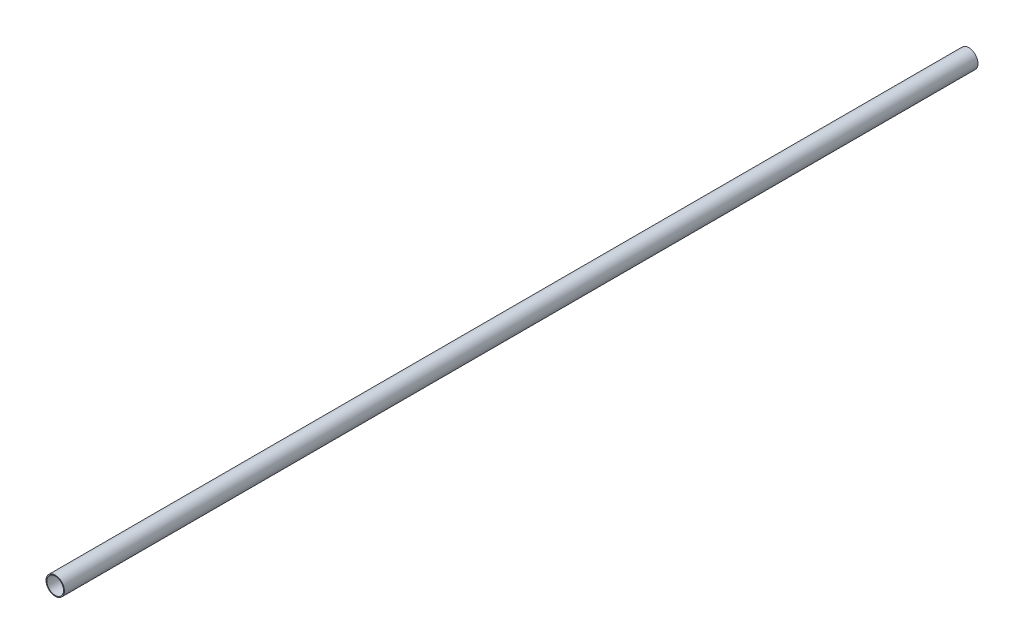
SolidWorks part; units mm, degrees
material "Thornel Mat VMA"
ref_plane "Front" through (0, 0, 0) normal (0, 0, 1) x (1, 0, 0)
ref_plane "Top" through (0, 0, 0) normal (0, 1, 0) x (1, 0, 0)
ref_plane "Right" through (0, 0, 0) normal (1, 0, 0) x (0, 0, -1)
sketch "Sketch1" plane through (0, 0, 0) normal (0, 0, 1) x (1, 0, 0)
  circle A0 centre (0, 0) radius 10.9601
  circle A1 centre (0, 0) radius 9.9441
  dimension "D1" = 21.9202
  dimension "D2" = 1.016
extrude "Boss-Extrude1" add sketch "Sketch1" along normal blind 1085.85
sketch "Sketch2" plane through (0, 0, 0) normal (0, 1, 0) x (1, 0, 0)
  line L0 (10.9601, 0) -> (13.8176, -1016) construction
  line L1 (13.8176, -1016) -> (10.9601, -1016) construction
  line L2 (10.9601, -1085.85) -> (10.9601, 0) construction
  line L3 (0, -1085.85) -> (0, 0) construction
  line L4 (10.9601, 0) -> (10.9601, -1016) construction
  dimension "D1" = 1016
  dimension "D2" = 13.8176
  dimension "D3" = 179.839
ref_plane "Plane1" through (0, 0, 1085.85) normal (0, 0, 1) x (1, 0, 0)
